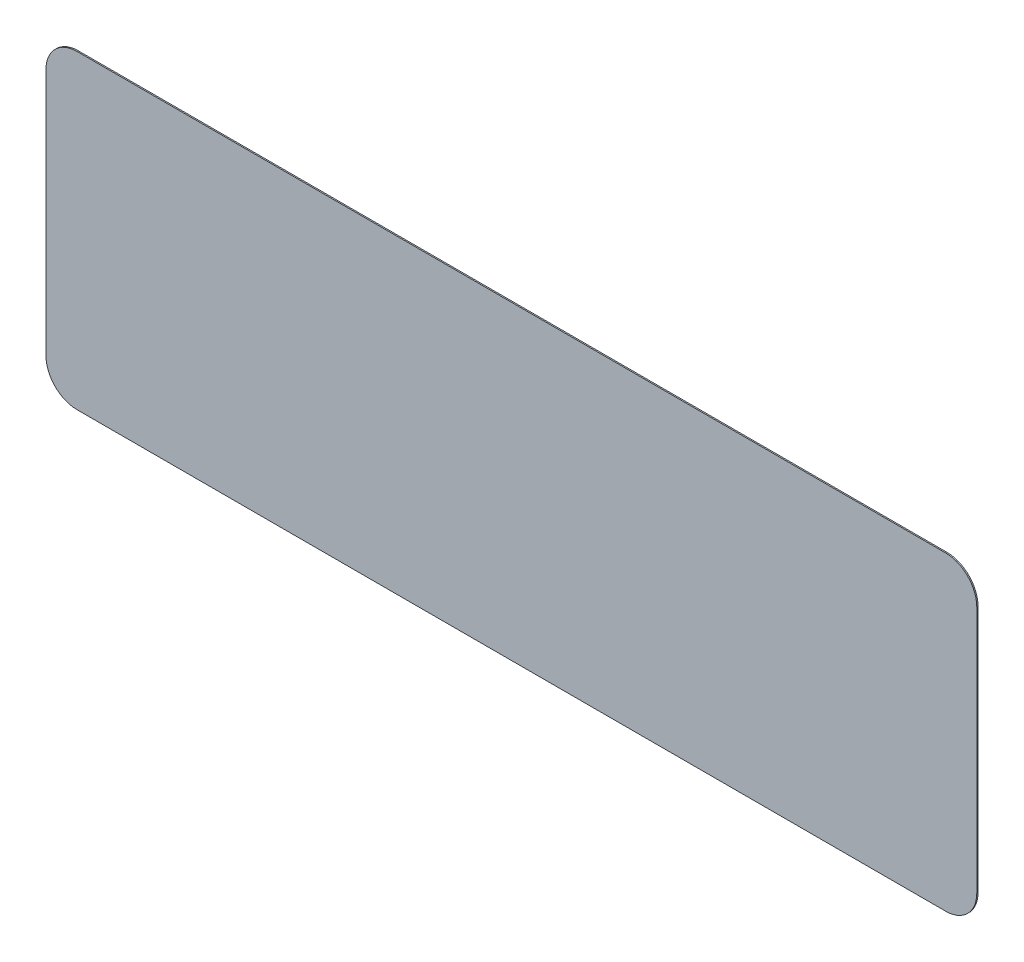
SolidWorks part; units mm, degrees
ref_plane "Front Plane" through (0, 0, 0) normal (0, 0, 1) x (1, 0, 0)
ref_plane "Top Plane" through (0, 0, 0) normal (0, 1, 0) x (1, 0, 0)
ref_plane "Right Plane" through (0, 0, 0) normal (1, 0, 0) x (0, 0, -1)
sketch "Sketch1" plane through (0, 0, 0) normal (0, 0, 1) x (1, 0, 0)
  line L1 (35.56, 12.7) -> (-35.56, 12.7)
  line L2 (38.1, 10.16) -> (38.1, -10.16)
  line L3 (35.56, -12.7) -> (-35.56, -12.7)
  line L4 (-38.1, 10.16) -> (-38.1, -10.16)
  line L5 (38.1, 12.7) -> (-38.1, -12.7) construction
  line L6 (38.1, -12.7) -> (-38.1, 12.7) construction
  arc A0 (-35.56, 12.7) -> (-38.1, 10.16) centre (-35.56, 10.16) ccw
  arc A1 (38.1, -10.16) -> (35.56, -12.7) centre (35.56, -10.16) cw
  arc A2 (35.56, 12.7) -> (38.1, 10.16) centre (35.56, 10.16) cw
  arc A3 (-35.56, -12.7) -> (-38.1, -10.16) centre (-35.56, -10.16) cw
  point P0 (0, 0)
  dimension "D3" = 2.54
  dimension "D1" = 76.2
  dimension "D2" = 25.4
extrude "Boss-Extrude1" add sketch "Sketch1" along normal blind 0.1016
